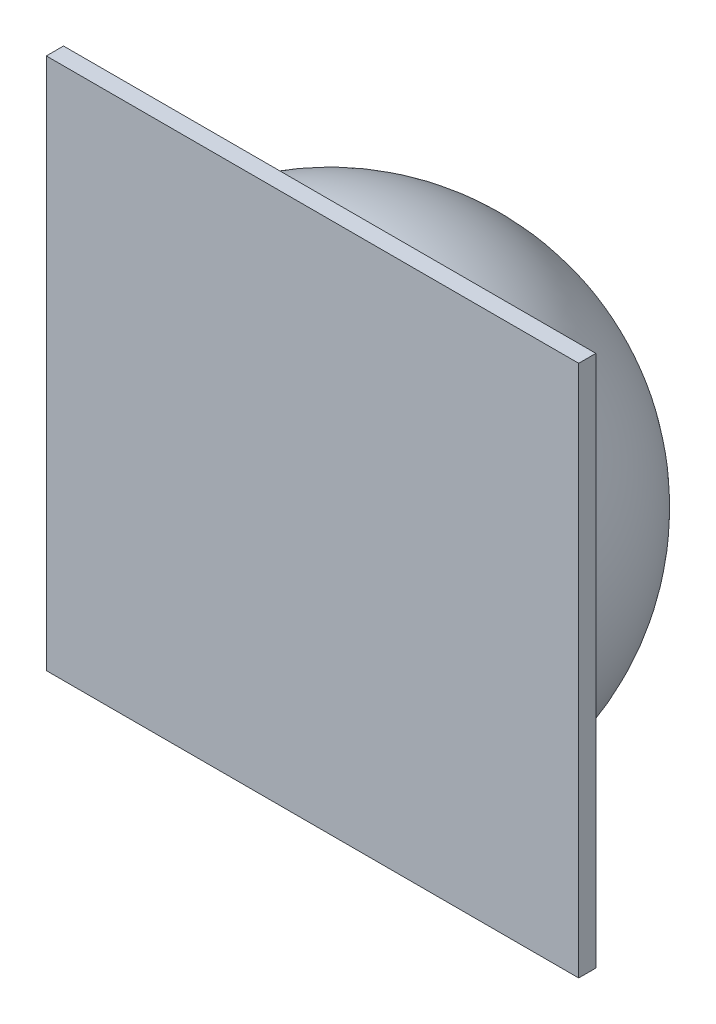
SolidWorks part; units mm, degrees
ref_plane "Front Plane" through (0, 0, 0) normal (0, 0, 1) x (1, 0, 0)
ref_plane "Top Plane" through (0, 0, 0) normal (0, 1, 0) x (1, 0, 0)
ref_plane "Right Plane" through (0, 0, 0) normal (1, 0, 0) x (0, 0, -1)
sketch "Sketch1" plane through (0, 0, 0) normal (0, 1, 0) x (1, 0, 0)
  line L0 (0, 14) -> (0, 0)
  line L1 (0, 0) -> (14, 0)
  arc A0 (14, 0) -> (0, 14) centre (0, 0) ccw
  dimension "D1" = 14
revolve "Revolve1" add sketch "Sketch1" angle 360 about L0
shell "Shell1" thickness 2
sketch "Sketch3" plane through (0, 0, 0) normal (0, 0, 1) x (1, 0, 0)
  line L1 (15.5, 15.5) -> (-15.5, 15.5)
  line L2 (15.5, 15.5) -> (15.5, -15.5)
  line L3 (15.5, -15.5) -> (-15.5, -15.5)
  line L4 (-15.5, 15.5) -> (-15.5, -15.5)
  line L5 (15.5, 15.5) -> (-15.5, -15.5) construction
  line L6 (15.5, -15.5) -> (-15.5, 15.5) construction
  point P0 (0, 0)
  dimension "D1" = 31
  dimension "D2" = 31
extrude "Boss-Extrude1" add sketch "Sketch3" along normal blind 1
